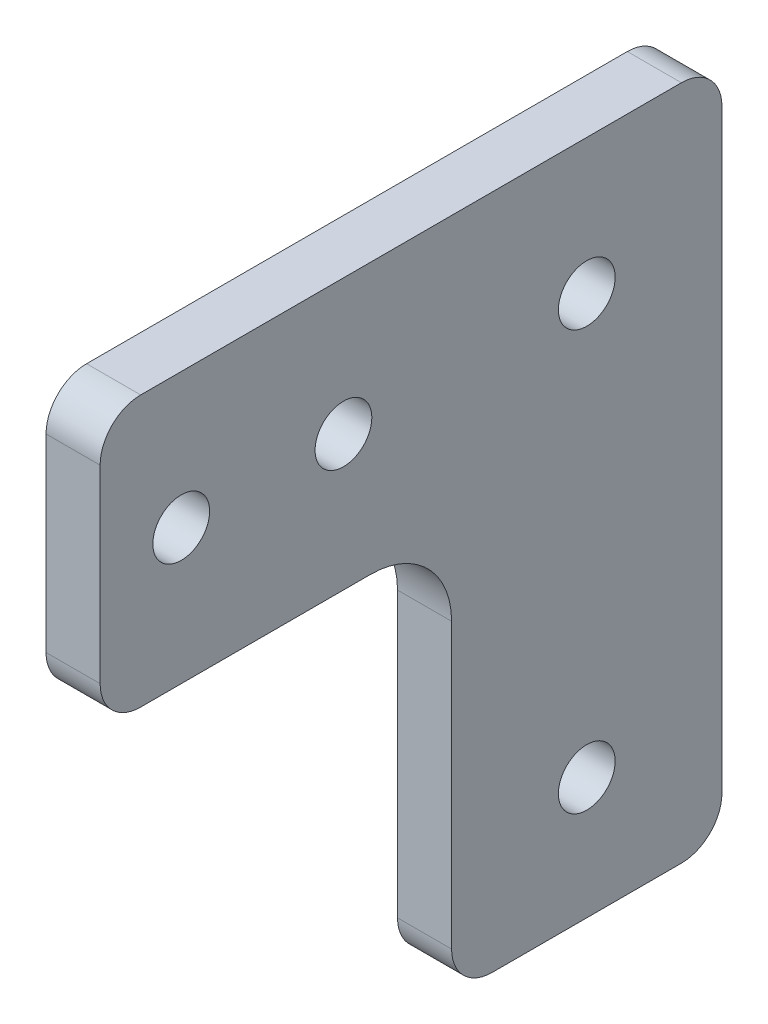
SolidWorks part; units mm, degrees
ref_plane "前视基准面" through (0, 0, 0) normal (0, 0, 1) x (1, 0, 0)
ref_plane "上视基准面" through (0, 0, 0) normal (0, 1, 0) x (1, 0, 0)
ref_plane "右视基准面" through (0, 0, 0) normal (1, 0, 0) x (0, 0, -1)
sketch "草图2" plane through (0, 0, 0) normal (1, 0, 0) x (0, 0, -1)
  line L0 (-211.25, 80.0417) -> (-171.25, 80.0417)
  line L1 (-168.25, 77.0417) -> (-168.25, 33.0417)
  line L2 (-171.25, 30.0417) -> (-185.25, 30.0417)
  line L3 (-188.25, 33.0417) -> (-188.25, 54.0417)
  line L4 (-194.25, 60.0417) -> (-211.25, 60.0417)
  line L5 (-214.25, 63.0417) -> (-214.25, 77.0417)
  arc A0 (-188.25, 54.0417) -> (-194.25, 60.0417) centre (-194.25, 54.0417) ccw
  arc A1 (-171.25, 80.0417) -> (-168.25, 77.0417) centre (-171.25, 77.0417) cw
  arc A2 (-214.25, 63.0417) -> (-211.25, 60.0417) centre (-211.25, 63.0417) ccw
  arc A3 (-214.25, 77.0417) -> (-211.25, 80.0417) centre (-211.25, 77.0417) cw
  arc A4 (-185.25, 30.0417) -> (-188.25, 33.0417) centre (-185.25, 33.0417) cw
  arc A5 (-171.25, 30.0417) -> (-168.25, 33.0417) centre (-171.25, 33.0417) ccw
  point P10 (-168.25, 80.0417)
  point P13 (-214.25, 60.0417)
  point P16 (-214.25, 80.0417)
  point P19 (-188.25, 30.0417)
  point P22 (-168.25, 30.0417)
  dimension "D5" = 6
  dimension "D6" = 3
  dimension "D7" = 3
  dimension "D8" = 3
  dimension "D1" = 46
  dimension "D2" = 50
  dimension "D3" = 20
  dimension "D4" = 20
extrude "凸台-拉伸1" add sketch "草图2" along normal blind 4
sketch "草图3" plane through (4, 0, 0) normal (1, 0, 0) x (0, 0, -1)
  line L0 (-178.25, 80.0417) -> (-178.25, 54.0417) construction
  line L2 (-178.25, 54.0417) -> (-178.25, 39.0417) construction
  line L3 (-171.25, 80.0417) -> (-211.25, 80.0417) construction
  line L4 (-208.25, 70.0417) -> (-198.35, 70.0417) construction
  line L5 (-214.25, 70.0417) -> (-208.25, 70.0417) construction
  line L6 (-214.25, 77.0417) -> (-214.25, 63.0417) construction
  circle A1 centre (-208.25, 70.0417) radius 2.1
  circle A2 centre (-178.25, 70.0417) radius 2.1
  circle A4 centre (-178.25, 39.0417) radius 2.1
  circle A5 centre (-196.25, 70.0417) radius 2.1
  point P6 (-178.25, 80.0417)
  point P16 (-196.25, 70.0417)
  dimension "D2" = 4.2
  dimension "D7" = 4.2
  dimension "D8" = 4.2
  dimension "D10" = 4.2
  dimension "D4" = 12
  dimension "D3" = 6
  dimension "D5" = 31
extrude "切除-拉伸1" cut sketch "草图3" against normal blind 10
equation "\"4。2\"=14.6455"
